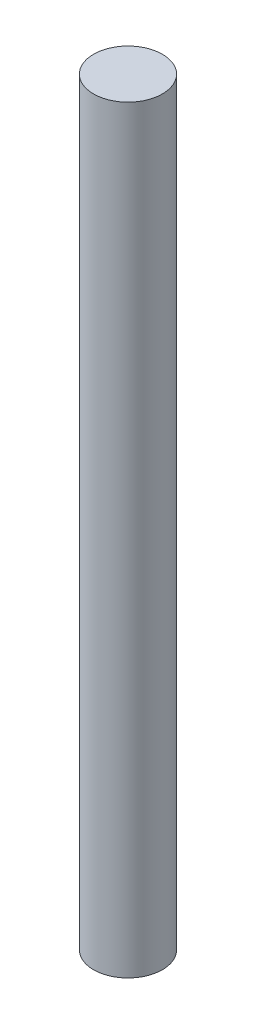
SolidWorks part; units mm, degrees
ref_plane "Front" through (0, 0, 0) normal (0, 0, 1) x (1, 0, 0)
ref_plane "Top" through (0, 0, 0) normal (0, 1, 0) x (1, 0, 0)
ref_plane "Right" through (0, 0, 0) normal (1, 0, 0) x (0, 0, -1)
sketch "Sketch1" plane through (0, 0, 0) normal (0, 1, 0) x (1, 0, 0)
  circle A0 centre (0, 0) radius 3.175
  dimension "D1" = 6.35
extrude "Boss-Extrude1" add sketch "Sketch1" along normal blind 70
